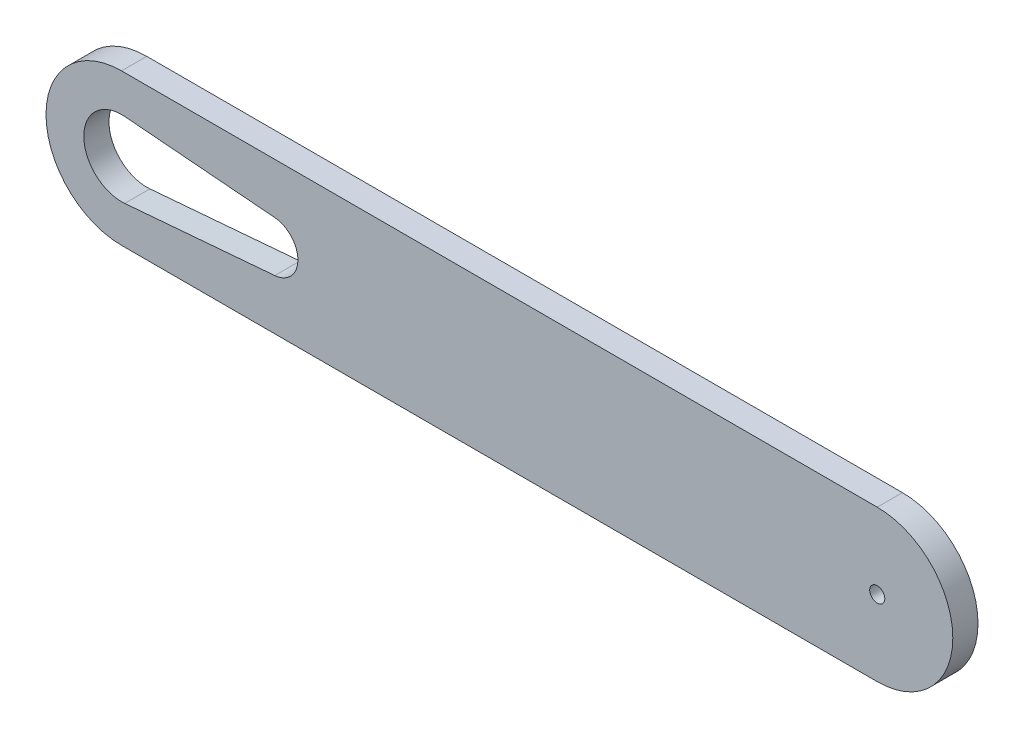
SolidWorks part; units mm, degrees
material "PVC 0.007 Plasticized"
ref_plane "Front Plane" through (0, 0, 0) normal (0, 0, 1) x (1, 0, 0)
ref_plane "Top Plane" through (0, 0, 0) normal (0, 1, 0) x (1, 0, 0)
ref_plane "Right Plane" through (0, 0, 0) normal (1, 0, 0) x (0, 0, -1)
sketch "Sketch1" plane through (0, 0, 0) normal (0, 0, 1) x (1, 0, 0)
  line L0 (-75, 0) -> (75, 0)
  dimension "D1" = 150
  dimension "D2" = 75
sketch "Sketch2" plane through (0, 0, 0) normal (0, 0, 1) x (1, 0, 0)
  line L0 (-75, 15) -> (75, 15)
  line L1 (-75, -15) -> (75, -15)
  arc A0 (-75, 15) -> (-75, -15) centre (-75, 0) ccw
  arc A1 (75, -15) -> (75, 15) centre (75, 0) ccw
  dimension "D1" = 30
  dimension "D2" = 30
extrude "Boss-Extrude1" add sketch "Sketch2" along normal blind 5
sketch "Sketch4" plane through (0, 0, 0) normal (0, 0, -1) x (-1, 0, 0)
  line L0 (75, 0) -> (-75, 0) construction
  line L1 (44.5833, 4.9826) -> (74.375, 7.4739)
  line L2 (44.5833, -4.9826) -> (74.375, -7.4739)
  arc A0 (74.375, -7.4739) -> (74.375, 7.4739) centre (75, 0) ccw
  circle A1 centre (-75, 0) radius 1.5
  arc A2 (44.5833, 4.9826) -> (44.5833, -4.9826) centre (45, 0) ccw
  dimension "D1" = 15
  dimension "D2" = 3
  dimension "D3" = 10
  dimension "D4" = 30
extrude "Cut-Extrude1" cut sketch "Sketch4" against normal blind 5
